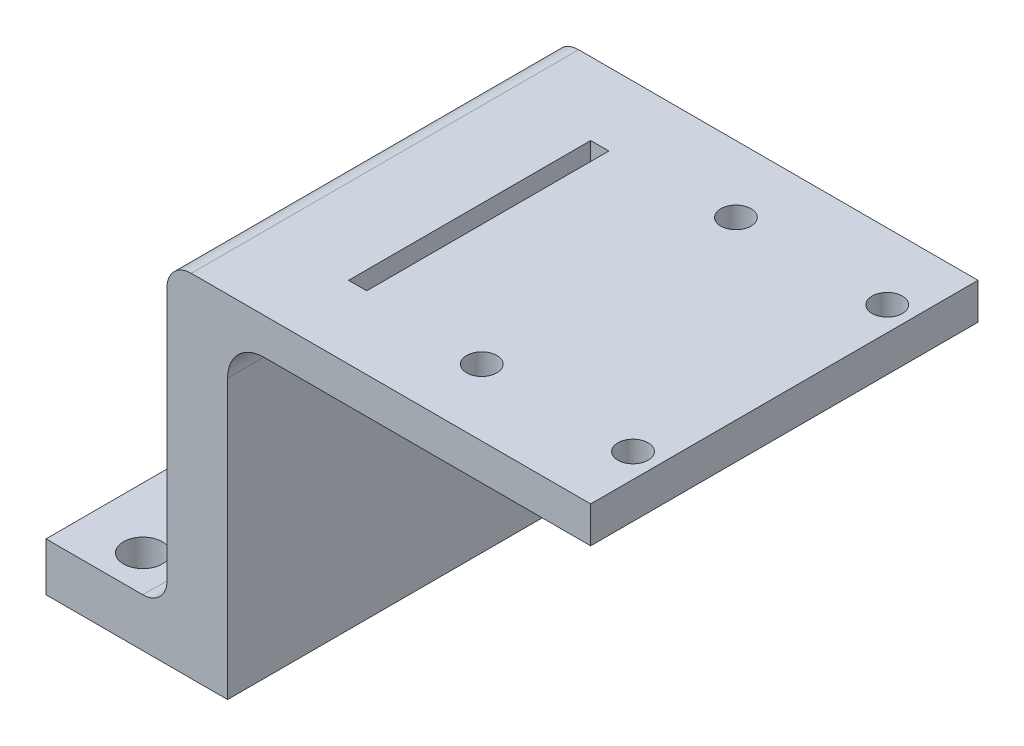
SolidWorks part; units mm, degrees
ref_plane "Front Plane" through (0, 0, 0) normal (0, 0, 1) x (1, 0, 0)
ref_plane "Top Plane" through (0, 0, 0) normal (0, 1, 0) x (1, 0, 0)
ref_plane "Right Plane" through (0, 0, 0) normal (1, 0, 0) x (0, 0, -1)
sketch "Sketch1" plane through (0, 0, 0) normal (0, 1, 0) x (1, 0, 0)
  line L1 (-5, 16) -> (5, 16)
  line L2 (-5, 16) -> (-5, -16)
  line L3 (-5, -16) -> (5, -16)
  line L4 (5, 16) -> (5, -16)
  line L5 (-5, 16) -> (5, -16) construction
  line L6 (-5, -16) -> (5, 16) construction
  circle A0 centre (0, -13) radius 1.6
  circle A1 centre (0, 13) radius 1.6
  point P0 (0, 0)
  dimension "D3" = 3.2
  dimension "D4" = 3.2
  dimension "D1" = 10
  dimension "D2" = 32
  dimension "D5" = 13
  dimension "D6" = 13
extrude "Boss-Extrude1" add sketch "Sketch1" along normal blind 4
sketch "Sketch2" plane through (5, 0, 0) normal (1, 0, 0) x (0, 0, -1)
  line L1 (-16, 4) -> (16, 4)
  line L2 (-16, 4) -> (-16, 0)
  line L3 (-16, 0) -> (16, 0)
  line L4 (16, 4) -> (16, 0)
extrude "Boss-Extrude2" add sketch "Sketch2" along normal blind 5
sketch "Sketch3" plane through (0, 4, 0) normal (0, 1, 0) x (1, 0, 0)
  line L0 (-5, -16) -> (10, -16) construction
  line L1 (10, 16) -> (5, 16)
  line L2 (10, 16) -> (10, -16)
  line L3 (10, -16) -> (5, -16)
  line L4 (5, 16) -> (5, -16)
  dimension "D1" = 5
extrude "Boss-Extrude3" add sketch "Sketch3" along normal blind 25
fillet "Fillet1" radius 2 1 edges at (5, 4, 0)
sketch "Sketch4" plane through (10, 0, 0) normal (1, 0, 0) x (0, 0, -1)
  line L0 (16, 0) -> (16, 29) construction
  line L1 (-16, 29) -> (16, 29)
  line L2 (-16, 29) -> (-16, 26)
  line L3 (-16, 26) -> (16, 26)
  line L4 (16, 29) -> (16, 26)
  dimension "D1" = 3
extrude "Boss-Extrude4" add sketch "Sketch4" along normal blind 30
sketch "Sketch5" plane through (0, 29, 0) normal (0, 1, 0) x (1, 0, 0)
  line L0 (5, 16) -> (5, -16) construction
  line L1 (16.5, 12.5) -> (39.5, 12.5) construction
  line L2 (16.5, 12.5) -> (16.5, -12.5) construction
  line L3 (16.5, -12.5) -> (39.5, -12.5) construction
  line L4 (39.5, 12.5) -> (39.5, -12.5) construction
  line L5 (16.5, 12.5) -> (39.5, -12.5) construction
  line L6 (16.5, -12.5) -> (39.5, 12.5) construction
  line L7 (25.5, 10.5) -> (38, 10.5) construction
  line L8 (25.5, 10.5) -> (25.5, -10.5) construction
  line L9 (25.5, -10.5) -> (38, -10.5) construction
  line L10 (38, 10.5) -> (38, -10.5) construction
  line L11 (25.5, 10.5) -> (38, -10.5) construction
  line L12 (25.5, -10.5) -> (38, 10.5) construction
  circle A0 centre (38, -10.5) radius 1.25
  circle A1 centre (38, 10.5) radius 1.25
  circle A2 centre (25.5, 10.5) radius 1.25
  circle A3 centre (25.5, -10.5) radius 1.25
  point P0 (28, 0)
  point P5 (31.75, 0)
  dimension "D8" = 2.5
  dimension "D1" = 25
  dimension "D2" = 23
  dimension "D3" = 21
  dimension "D4" = 12.5
  dimension "D5" = 0
  dimension "D6" = 9
  dimension "D7" = 23
  dimension "D9" = 0
extrude "Cut-Extrude1" cut sketch "Sketch5" against normal blind 25
fillet "Fillet2" radius 2 1 edges at (5, 29, 0)
fillet "Fillet3" radius 3 1 edges at (10, 26, 0)
sketch "Sketch7" plane through (0, 26, 0) normal (0, -1, 0) x (1, 0, 0)
  line L0 (16.5, 0) -> (5.8692, 0) construction
  line L1 (16.5, -12.5) -> (16.5, 12.5) construction
  line L3 (14, 10) -> (15.5, 10)
  line L4 (14, 10) -> (14, -10)
  line L5 (14, -10) -> (15.5, -10)
  line L6 (15.5, 10) -> (15.5, -10)
  line L7 (14, 10) -> (15.5, -10) construction
  line L8 (14, -10) -> (15.5, 10) construction
  point P5 (14.75, 0)
  dimension "D1" = 1
  dimension "D2" = 1.5
  dimension "D3" = 20
extrude "Cut-Extrude2" cut sketch "Sketch7" against normal blind 10
